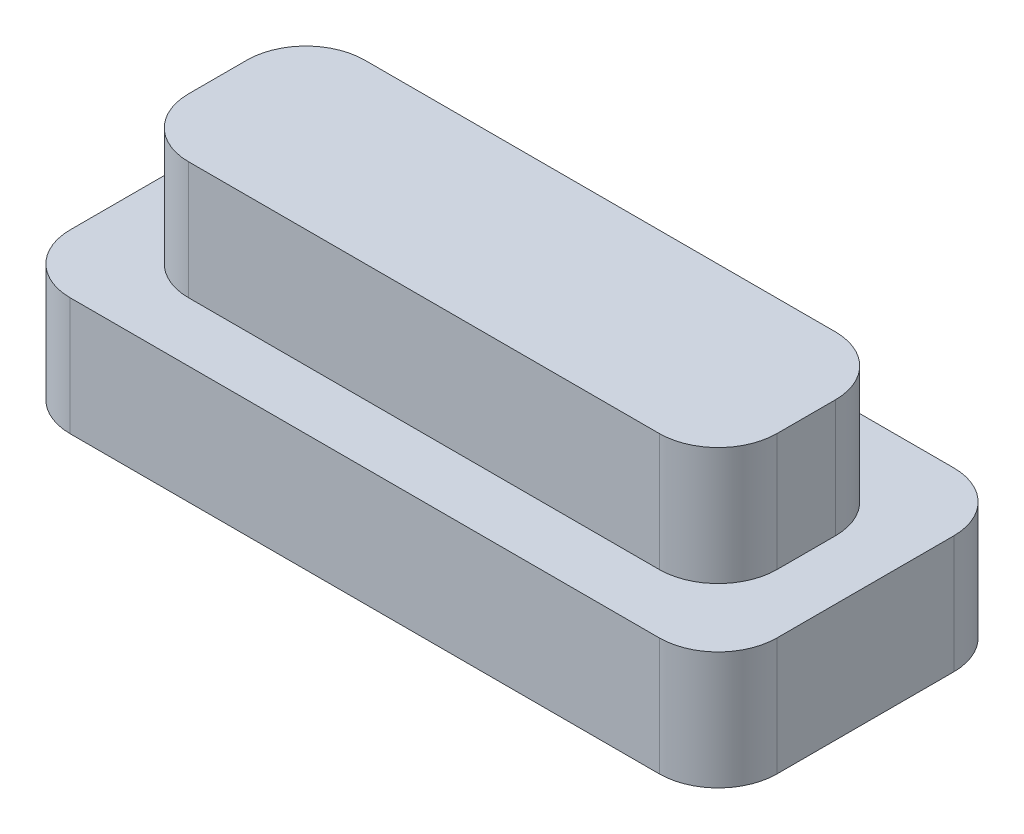
SolidWorks part; units mm, degrees
ref_plane "Front Plane" through (0, 0, 0) normal (0, 0, 1) x (1, 0, 0)
ref_plane "Top Plane" through (0, 0, 0) normal (0, 1, 0) x (1, 0, 0)
ref_plane "Right Plane" through (0, 0, 0) normal (1, 0, 0) x (0, 0, -1)
sketch "Sketch1" plane through (0, 0, 0) normal (0, 1, 0) x (1, 0, 0)
  line L1 (-5, 2.5) -> (5, 2.5)
  line L2 (-6, 1.5) -> (-6, -1.5)
  line L3 (-5, -2.5) -> (5, -2.5)
  line L4 (6, 1.5) -> (6, -1.5)
  line L5 (-6, 2.5) -> (6, -2.5) construction
  line L6 (-6, -2.5) -> (6, 2.5) construction
  arc A0 (-6, 1.5) -> (-5, 2.5) centre (-5, 1.5) cw
  arc A1 (6, 1.5) -> (5, 2.5) centre (5, 1.5) ccw
  arc A2 (-5, -2.5) -> (-6, -1.5) centre (-5, -1.5) cw
  arc A3 (5, -2.5) -> (6, -1.5) centre (5, -1.5) ccw
  point P0 (0, 0)
  dimension "D3" = 1
  dimension "D4" = 1
  dimension "D5" = 1
  dimension "D6" = 1
  dimension "D1" = 12
  dimension "D2" = 5
extrude "Boss-Extrude1" add sketch "Sketch1" along normal blind 2
sketch "Sketch2" plane through (0, 2, 0) normal (0, 1, 0) x (1, 0, 0)
  line L1 (-3.995, 1.495) -> (3.995, 1.495)
  line L2 (-4.995, 0.495) -> (-4.995, -0.495)
  line L3 (-3.995, -1.495) -> (3.995, -1.495)
  line L4 (4.995, 0.495) -> (4.995, -0.495)
  line L5 (-4.995, 1.495) -> (4.995, -1.495) construction
  line L6 (-4.995, -1.495) -> (4.995, 1.495) construction
  arc A0 (3.995, 1.495) -> (4.995, 0.495) centre (3.995, 0.495) cw
  arc A1 (-4.995, 0.495) -> (-3.995, 1.495) centre (-3.995, 0.495) cw
  arc A2 (-3.995, -1.495) -> (-4.995, -0.495) centre (-3.995, -0.495) cw
  arc A3 (3.995, -1.495) -> (4.995, -0.495) centre (3.995, -0.495) ccw
  point P0 (0, 0)
  dimension "D3" = 1
  dimension "D4" = 1
  dimension "D5" = 1
  dimension "D6" = 1
  dimension "D1" = 9.99
  dimension "D2" = 2.99
extrude "Boss-Extrude2" add sketch "Sketch2" along normal blind 2 contours A3 L3 A2 L2 A1 L1 A0 L4
